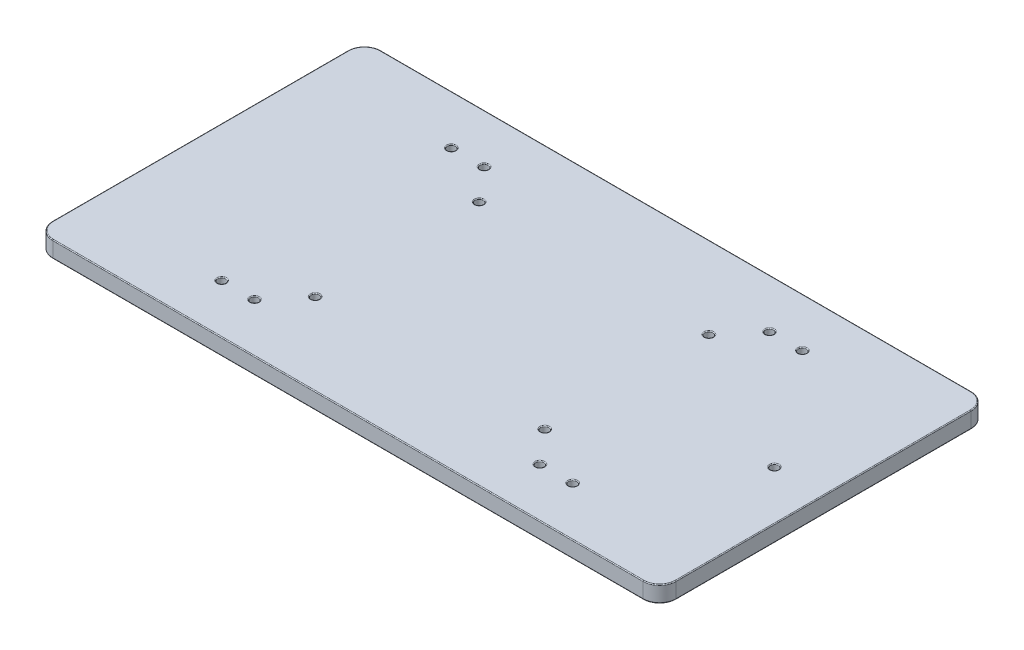
SolidWorks part; units mm, degrees
ref_plane "Front Plane" through (0, 0, 0) normal (0, 0, 1) x (1, 0, 0)
ref_plane "Top Plane" through (0, 0, 0) normal (0, 1, 0) x (1, 0, 0)
ref_plane "Right Plane" through (0, 0, 0) normal (1, 0, 0) x (0, 0, -1)
sketch "Sketch1" plane through (0, 0, 0) normal (0, 1, 0) x (1, 0, 0)
  line L0 (80, 50) -> (80, -50) construction
  line L1 (-95, -50) -> (95, -50)
  line L2 (-95, -50) -> (-95, 50)
  line L3 (-95, 50) -> (95, 50)
  line L4 (95, -50) -> (95, 50)
  line L5 (-95, -50) -> (95, 50) construction
  line L6 (-95, 50) -> (95, -50) construction
  line L7 (-35, 25) -> (35, 25) construction
  line L8 (-35, 25) -> (-35, -25) construction
  line L9 (-35, -25) -> (35, -25) construction
  line L10 (35, 25) -> (35, -25) construction
  line L11 (-35, 25) -> (35, -25) construction
  line L12 (-35, -25) -> (35, 25) construction
  line L13 (0, 0) -> (22.9192, 0) construction
  line L14 (0, 0) -> (0, 7.5583) construction
  circle A0 centre (-35, 25) radius 1.25
  circle A1 centre (35, 25) radius 1.25
  circle A2 centre (35, -25) radius 1.25
  circle A3 centre (-35, -25) radius 1.25
  circle A4 centre (80, 0) radius 1.25
  circle A5 centre (-53.5, -35) radius 1.25
  circle A6 centre (-43.5, -35) radius 1.25
  circle A7 centre (-53.5, 35) radius 1.25
  circle A8 centre (-43.5, 35) radius 1.25
  circle A9 centre (53.5, -35) radius 1.25
  circle A10 centre (43.5, -35) radius 1.25
  circle A11 centre (53.5, 35) radius 1.25
  circle A12 centre (43.5, 35) radius 1.25
  point P0 (0, 0)
  point P6 (0, 0)
  dimension "D5" = 2.5
  dimension "D7" = 2.5
  dimension "D8" = 2.5
  dimension "D1" = 190
  dimension "D2" = 100
  dimension "D3" = 70
  dimension "D4" = 50
  dimension "D6" = 15
  dimension "D9" = 10
  dimension "D10" = 43.5
  dimension "D11" = 15
extrude "Boss-Extrude1" add sketch "Sketch1" along normal blind 5
fillet "Fillet1" radius 5 4 edges at (-95, 2.5, 50) (-95, 2.5, -50) (95, 2.5, -50) (95, 2.5, 50)
fillet "Fillet2" radius 0.25 42 edges at (43.5, 0, -33.75) (43.5, 5, -33.75) (53.5, 0, -33.75) (53.5, 5, -33.75) (43.5, 0, 33.75) (43.5, 5, 33.75) (53.5, 0, 33.75) (53.5, 5, 33.75) (-43.5, 0, -36.25) (-43.5, 5, -36.25) (-53.5, 0, -36.25) (-53.5, 5, -36.25) (-43.5, 0, 36.25) (-43.5, 5, 36.25) (-53.5, 0, 36.25) (-53.5, 5, 36.25) (80, 0, 1.25) (80, 5, 1.25) (-35, 0, 26.25) (-35, 5, 26.25) (35, 0, 26.25) (35, 5, 26.25) (35, 0, -23.75) (35, 5, -23.75) (-35, 0, -23.75) (-35, 5, -23.75) (95, 0, 0) (0, 0, -50) (-95, 0, 0) (0, 0, 50) (95, 5, 0) (0, 5, -50) (-95, 5, 0) (93.5355, 0, 48.5355) (93.5355, 0, -48.5355) (-93.5355, 0, -48.5355) (-93.5355, 0, 48.5355) (93.5355, 5, 48.5355) (93.5355, 5, -48.5355) (-93.5355, 5, -48.5355) (-93.5355, 5, 48.5355) (0, 5, 50)
